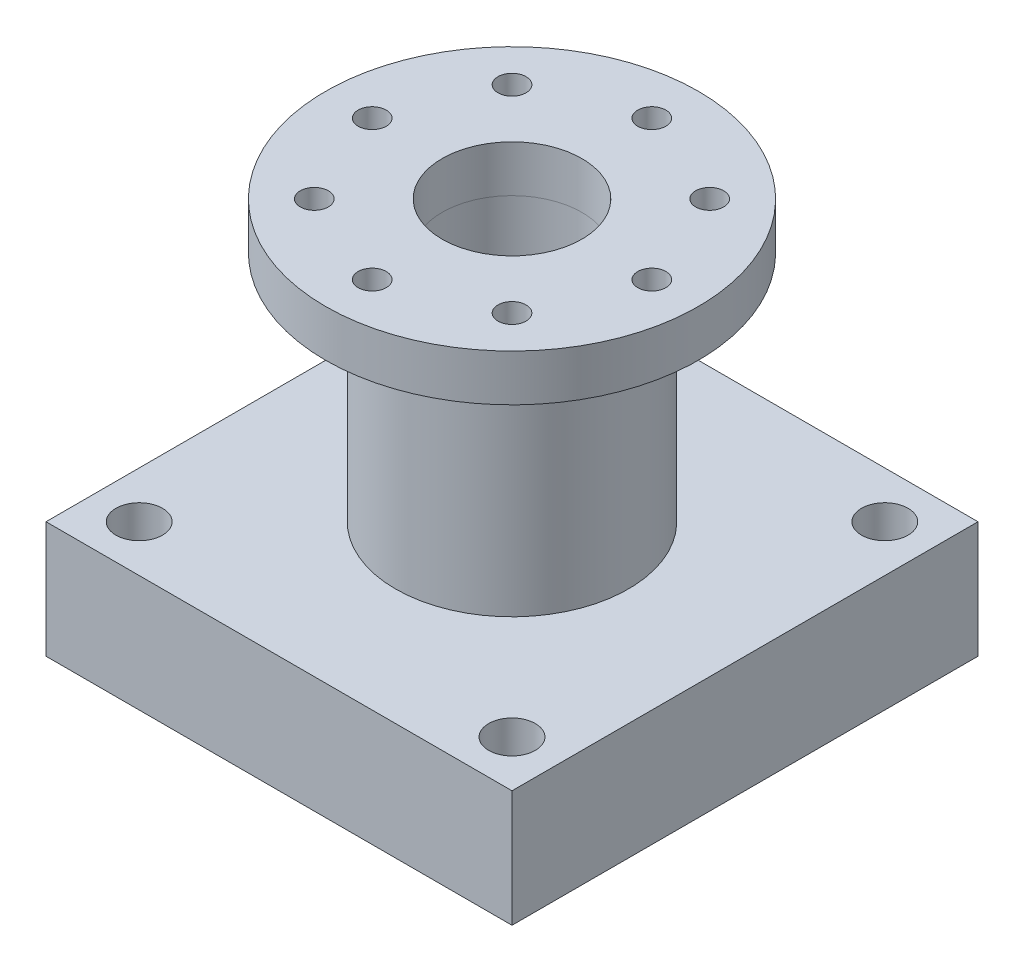
SolidWorks part; units mm, degrees
ref_plane "Front Plane" through (0, 0, 0) normal (0, 0, 1) x (1, 0, 0)
ref_plane "Top Plane" through (0, 0, 0) normal (0, 1, 0) x (1, 0, 0)
ref_plane "Right Plane" through (0, 0, 0) normal (1, 0, 0) x (0, 0, -1)
sketch "Sketch1" plane through (0, 0, 0) normal (0, 1, 0) x (1, 0, 0)
  line L1 (-50, -50) -> (50, -50)
  line L2 (-50, -50) -> (-50, 50)
  line L3 (-50, 50) -> (50, 50)
  line L4 (50, -50) -> (50, 50)
  line L5 (-50, -50) -> (50, 50) construction
  line L6 (-50, 50) -> (50, -50) construction
  point P0 (0, 0)
  dimension "D1" = 100
  dimension "D2" = 100
extrude "Boss-Extrude1" add sketch "Sketch1" against normal blind 25
sketch "Sketch2" plane through (0, 0, 0) normal (0, 1, 0) x (1, 0, 0)
  circle A0 centre (0, 0) radius 25
  circle A1 centre (0, 0) radius 15
  dimension "D1" = 50
  dimension "D2" = 10
extrude "Boss-Extrude2" add sketch "Sketch2" along normal blind 50
sketch "Sketch3" plane through (0, 50, 0) normal (0, 1, 0) x (1, 0, 0)
  circle A0 centre (0, 0) radius 40
  circle A1 centre (0, 0) radius 15
  dimension "D1" = 80
extrude "Boss-Extrude3" add sketch "Sketch3" along normal blind 10 separate body
sketch "Sketch4" plane through (0, 60, 0) normal (0, 1, 0) x (1, 0, 0)
  circle A0 centre (0, 30) radius 3.0144
  dimension "D1" = 30
extrude "Cut-Extrude1" cut sketch "Sketch4" against normal up to next (10 mm away)
pattern_circular "CirPattern1" count 8 over 360 about axis through (0, 0, 0) along (0, 1, 0) of "Cut-Extrude1"
sketch "Sketch5" plane through (0, -25, 0) normal (0, -1, 0) x (1, 0, 0)
  line L0 (-50, 50) -> (50, 50) construction
  line L1 (-50, -50) -> (-50, 50) construction
  circle A0 centre (-40, 40) radius 5
  dimension "D3" = 10
  dimension "D1" = 10
  dimension "D2" = 10
extrude "Cut-Extrude2" cut sketch "Sketch5" against normal up to next (25 mm away)
pattern_linear "LPattern1" count 2 spacing 80 along (0, 0, -1) count 2 spacing 80 along (1, 0, 0) of "Cut-Extrude2"
